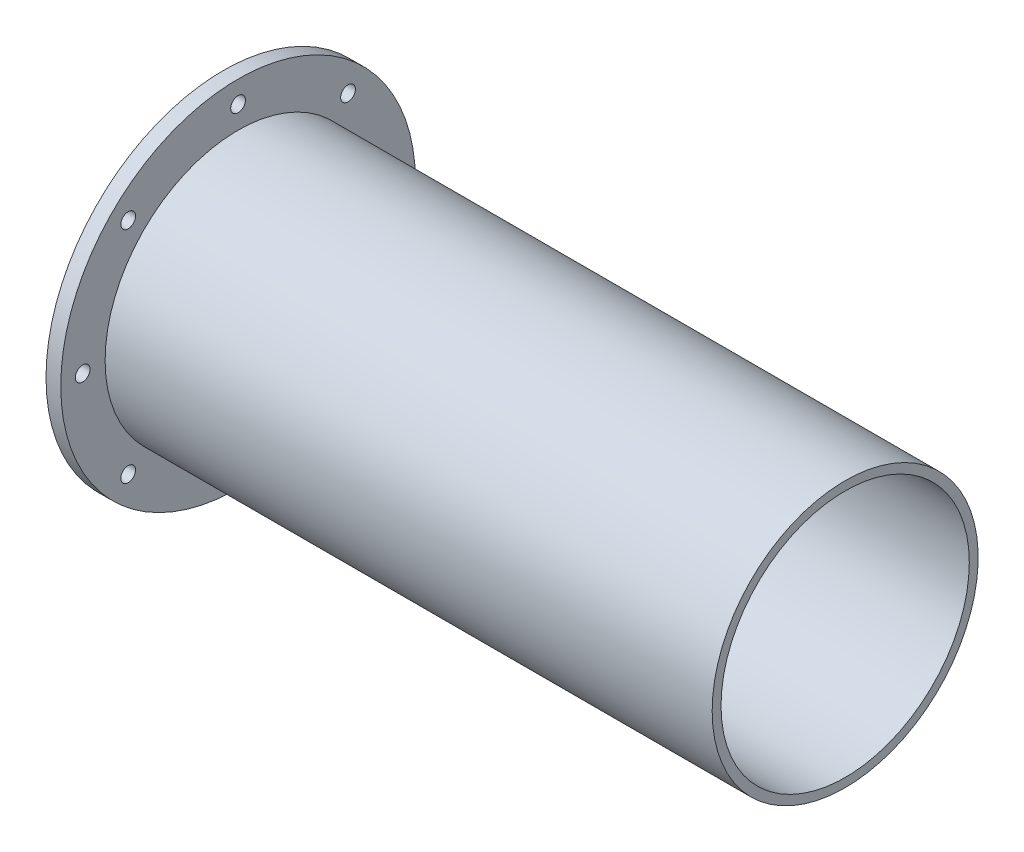
SolidWorks part; units mm, degrees
ref_plane "Front Plane" through (0, 0, 0) normal (0, 0, 1) x (1, 0, 0)
ref_plane "Top Plane" through (0, 0, 0) normal (0, 1, 0) x (1, 0, 0)
ref_plane "Right Plane" through (0, 0, 0) normal (1, 0, 0) x (0, 0, -1)
sketch "Sketch1" plane through (0, 0, 0) normal (0, 0, 1) x (1, 0, 0)
  line L1 (0, 76.2) -> (6.35, 76.2)
  line L2 (6.35, 76.2) -> (6.35, 57.15)
  line L3 (6.35, 57.15) -> (267.208, 57.15)
  line L4 (267.208, 57.15) -> (267.208, 53.34)
  line L5 (267.208, 53.34) -> (0, 53.34)
  line L8 (0, 0) -> (267.208, 0) construction
  line L9 (267.208, 0) -> (267.208, 53.34) construction
  line L10 (0, 76.2) -> (0, 53.34)
  dimension "External Diameter" = 114.3
  dimension "Screwing Space Section" = 6.35
  dimension "Comp" = 152.4
  dimension "Shell Length" = 267.208
  dimension "Wall Thickness" = 3.81
revolve "Revolve1" add sketch "Sketch1" angle 360 about L8
sketch "Sketch2" plane through (6.35, 0, 0) normal (1, 0, 0) x (0, 0, -1)
  line L0 (0, 0) -> (66.802, 0) construction
  circle A0 centre (66.802, 0) radius 3.175
  dimension "Screw Hole Diameter" = 6.35
  dimension "Screw Hole Distance" = 66.802
extrude "Cut-Extrude1" cut sketch "Sketch2" against normal through all
pattern_circular "CirPattern1" count 8 over 360 about axis through (0, 0, 0) along (-1, 0, 0) of "Cut-Extrude1"
